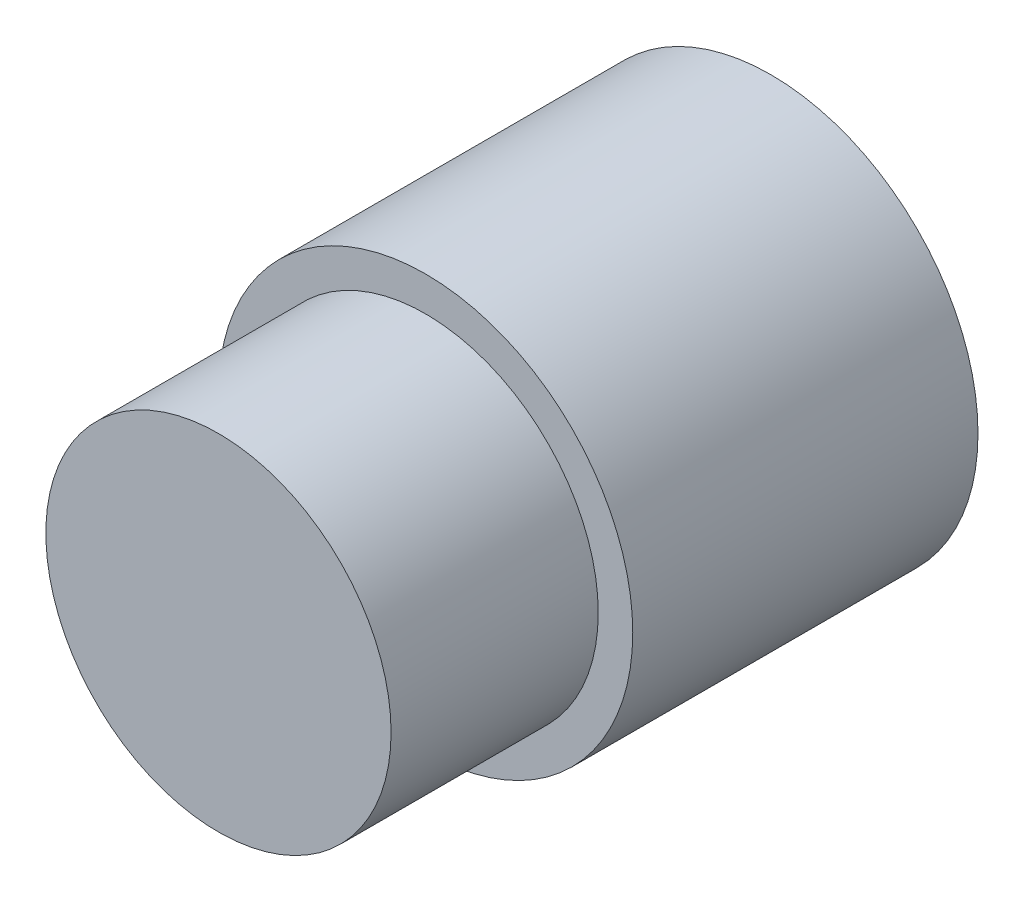
SolidWorks part; units mm, degrees
ref_plane "Piano frontale" through (0, 0, 0) normal (0, 0, 1) x (1, 0, 0)
ref_plane "Piano superiore" through (0, 0, 0) normal (0, 1, 0) x (1, 0, 0)
ref_plane "Piano destro" through (0, 0, 0) normal (1, 0, 0) x (0, 0, -1)
sketch "Schizzo1" plane through (0, 0, 0) normal (0, 0, 1) x (1, 0, 0)
  circle A0 centre (0, 0) radius 3
  dimension "D1" = 6
extrude "Estrusione-Estrusione1" add sketch "Schizzo1" along normal blind 5
sketch "Schizzo2" plane through (0, 0, 5) normal (0, 0, 1) x (1, 0, 0)
  circle A0 centre (0, 0) radius 2.5
  dimension "D1" = 5
extrude "Estrusione-Estrusione2" add sketch "Schizzo2" along normal blind 3
